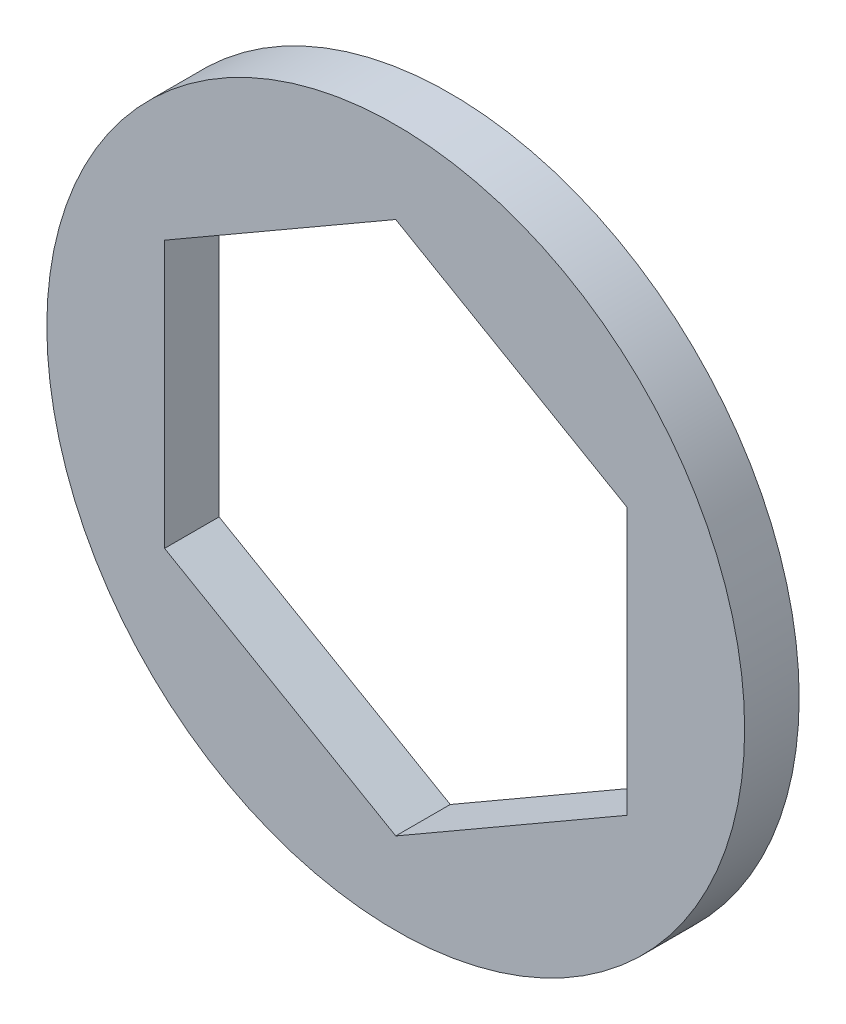
SolidWorks part; units mm, degrees
material "Nylon 101"
ref_plane "Front Plane" through (0, 0, 0) normal (0, 0, 1) x (1, 0, 0)
ref_plane "Top Plane" through (0, 0, 0) normal (0, 1, 0) x (1, 0, 0)
ref_plane "Right Plane" through (0, 0, 0) normal (1, 0, 0) x (0, 0, -1)
sketch "Sketch1" plane through (0, 0, 0) normal (0, 0, 1) x (1, 0, 0)
  line L1 (0, 7.7723) -> (-6.731, 3.8861)
  line L2 (-6.731, 3.8861) -> (-6.731, -3.8861)
  line L3 (-6.731, -3.8861) -> (0, -7.7723)
  line L4 (0, -7.7723) -> (6.731, -3.8861)
  line L5 (6.731, -3.8861) -> (6.731, 3.8861)
  line L6 (6.731, 3.8861) -> (0, 7.7723)
  circle A0 centre (0, 0) radius 10.16
  circle A1 centre (0, 0) radius 6.731 construction
  dimension "D1" = 13.462
  dimension "D2" = 20.32
extrude "Boss-Extrude1" add sketch "Sketch1" along normal mid plane 1.5875
